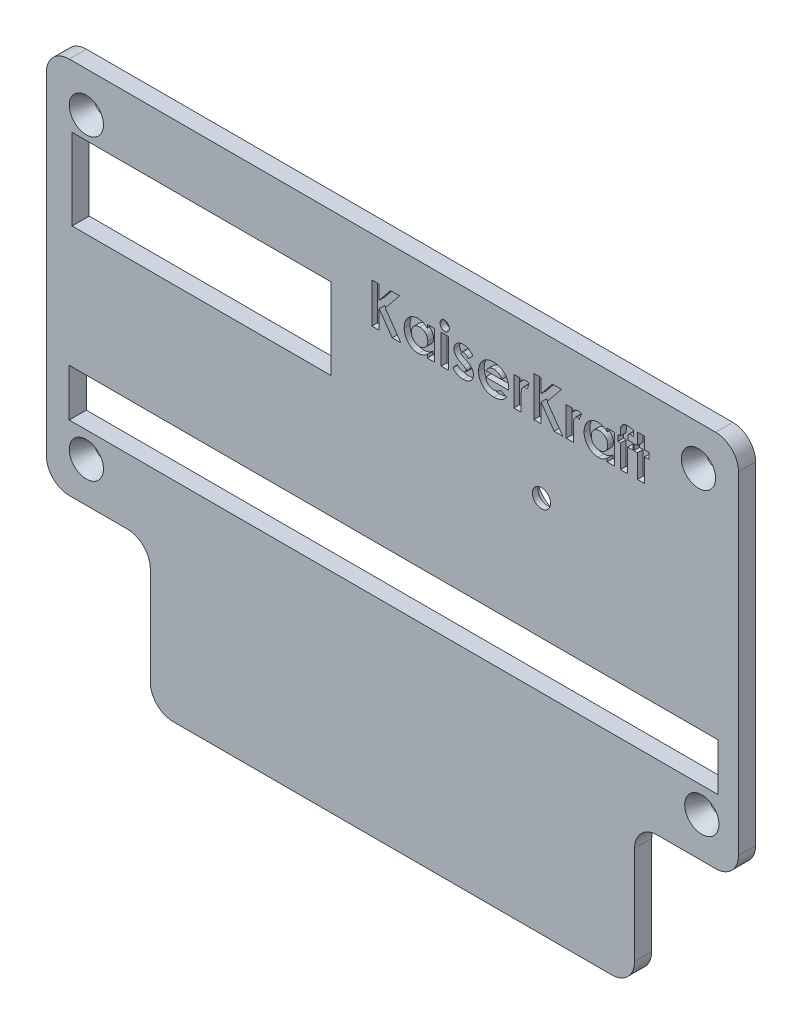
SolidWorks part; units mm, degrees
ref_plane "Płaszczyzna przednia" through (0, 0, 0) normal (0, 0, 1) x (1, 0, 0)
ref_plane "Płaszczyzna górna" through (0, 0, 0) normal (0, 1, 0) x (1, 0, 0)
ref_plane "Płaszczyzna prawa" through (0, 0, 0) normal (1, 0, 0) x (0, 0, -1)
sketch "Szkic1" plane through (0, 0, 0) normal (0, 0, 1) x (1, 0, 0)
  line L0 (3, -3.2) -> (3, 63)
  line L1 (3, 63) -> (-118.2, 63)
  line L2 (-118.2, 63) -> (-118.2, -3.2)
  line L3 (-118.2, -3.2) -> (-100, -3.2)
  line L4 (-100, -3.2) -> (-100, -28.4)
  line L5 (-100, -28.4) -> (-15.2, -28.4)
  line L6 (-15.2, -28.4) -> (-15.2, -3.2)
  line L7 (-15.2, -3.2) -> (3, -3.2)
  point P16 (0, 0)
  point P17 (0, 0)
  point P18 (0, 0)
  point P19 (0, 0)
  point P20 (0, 0)
  point P21 (0, 0)
  point P22 (0, 0)
  point P23 (0, 0)
  dimension "D2" = 66.2
  dimension "D3" = 18.2
  dimension "D4" = 121.2
  dimension "D5" = 25.2
extrude "Dodanie-wyciągnięcie1" add sketch "Szkic1" along normal blind 3
sketch "Szkic2" plane through (0, 0, 3) normal (0, 0, 1) x (1, 0, 0)
  line L0 (-118.2, 12.4) -> (3, 12.4) construction
  line L1 (-68.4, 37.925) -> (-113.7, 37.925)
  line L2 (-68.4, 37.925) -> (-68.4, 52.125)
  line L3 (-68.4, 52.125) -> (-113.7, 52.125)
  line L4 (-113.7, 37.925) -> (-113.7, 52.125)
  line L5 (-118.2, 63) -> (-118.2, -3.2) construction
  line L6 (3, -3.2) -> (3, 63) construction
  line L7 (-15.2, -3.2) -> (3, -3.2) construction
  line L8 (3, 63) -> (-118.2, 63) construction
  line L10 (-114.2, 16.55) -> (-0.6, 16.55)
  line L11 (-114.2, 16.55) -> (-114.2, 8.25)
  line L12 (-114.2, 8.25) -> (-0.6, 8.25)
  line L13 (-0.6, 16.55) -> (-0.6, 8.25)
  circle A0 centre (-31.5, 37.75) radius 1.6
  point P14 (-113.7, 45.025)
  point P19 (-31.5, 37.75)
  dimension "D11" = 3.2
  dimension "D1" = 15.6
  dimension "D2" = 4.5
  dimension "D3" = 10.875
  dimension "D4" = 14.2
  dimension "D5" = 45.3
  dimension "D6" = 4
  dimension "D7" = 3.6
  dimension "D8" = 8.3
  dimension "D9" = 25.25
  dimension "D10" = 34.5
extrude "Wytnij-wyciągnięcie1" cut sketch "Szkic2" against normal blind 3
sketch "Szkic3" plane through (0, 0, 0) normal (0, 0, -1) x (-1, 0, 0)
  circle A0 centre (31.5, 37.75) radius 3.75
  dimension "D1" = 7.5
extrude "Wytnij-wyciągnięcie2" cut sketch "Szkic3" against normal blind 2
sketch "Szkic4" plane through (0, 0, 3) normal (0, 0, 1) x (1, 0, 0)
  line L0 (-118.2, 63) -> (-118.2, -3.2) construction
  line L1 (-118.2, -3.2) -> (-100, -3.2) construction
  line L2 (3, 63) -> (-118.2, 63) construction
  line L3 (3, -3.2) -> (3, 63) construction
  line L4 (-15.2, -3.2) -> (3, -3.2) construction
  circle A0 centre (-111.2, 56) radius 1.5
  circle A1 centre (-111.2, 3.8) radius 1.5
  circle A2 centre (-3.4175, 3.8) radius 1.5
  circle A3 centre (-4, 56) radius 1.5
  point P0 (-111.2, 3.8)
  point P1 (-111.2, 56)
  point P2 (-4, 56)
  point P3 (-3.4175, 3.8)
  dimension "D8" = 3
  dimension "D1" = 7
  dimension "D2" = 7
  dimension "D3" = 7
  dimension "D4" = 7
  dimension "D5" = 7
  dimension "D6" = 7
  dimension "D7" = 7
  dimension "D9" = 7
extrude "Wytnij-wyciągnięcie3" cut sketch "Szkic4" against normal through all
sketch "Szkic5" plane through (0, 0, 3) normal (0, 0, 1) x (1, 0, 0)
  circle A0 centre (-111.2, 56) radius 3
  dimension "D1" = 6
loft "Wycięcie-wyciągnięcie po profilach5" cut section "Szkic5" section edge at (-109.7, 56, 0)
sketch "Szkic14" plane through (0, 0, 3) normal (0, 0, 1) x (1, 0, 0)
  circle A0 centre (-111.2, 3.8) radius 3
  dimension "D1" = 6
sketch "Szkic15" plane through (0, 0, 3) normal (0, 0, 1) x (1, 0, 0)
  circle A0 centre (-3.4175, 3.8) radius 3
  dimension "D1" = 6
sketch "Szkic16" plane through (0, 0, 3) normal (0, 0, 1) x (1, 0, 0)
  circle A0 centre (-4, 56) radius 3
  dimension "D1" = 6
loft "Wycięcie-wyciągnięcie po profilach6" cut profiles "Szkic14" section edge at (-109.7, 3.8, 0) section "Szkic14"
loft "Wycięcie-wyciągnięcie po profilach7" cut profiles "Szkic15" section edge at (-1.9175, 3.8, 0) section "Szkic15"
loft "Wycięcie-wyciągnięcie po profilach8" cut profiles "Szkic16" section edge at (-2.5, 56, 0) section "Szkic16"
fillet "Zaokrąglenie1" radius 4 8 edges at (-100, -28.4, 1.5) (-100, -3.2, 1.5) (-118.2, -3.2, 1.5) (-118.2, 63, 1.5) (3, 63, 1.5) (-15.2, -3.2, 1.5) (3, -3.2, 1.5) (-15.2, -28.4, 1.5)
sketch "Szkic17" plane through (0, 0, 3) normal (0, 0, 1) x (1, 0, 0)
  line L0 (-1, 63) -> (-114.2, 63) construction
  line L1 (3, 0.8) -> (3, 59) construction
  text T0 "<b>KaiserKraft</b>" font "Century Gothic" height 7
  dimension "D1" = 14
  dimension "D2" = 65
extrude "Wytnij-wyciągnięcie5" cut sketch "Szkic17" against normal blind 1
